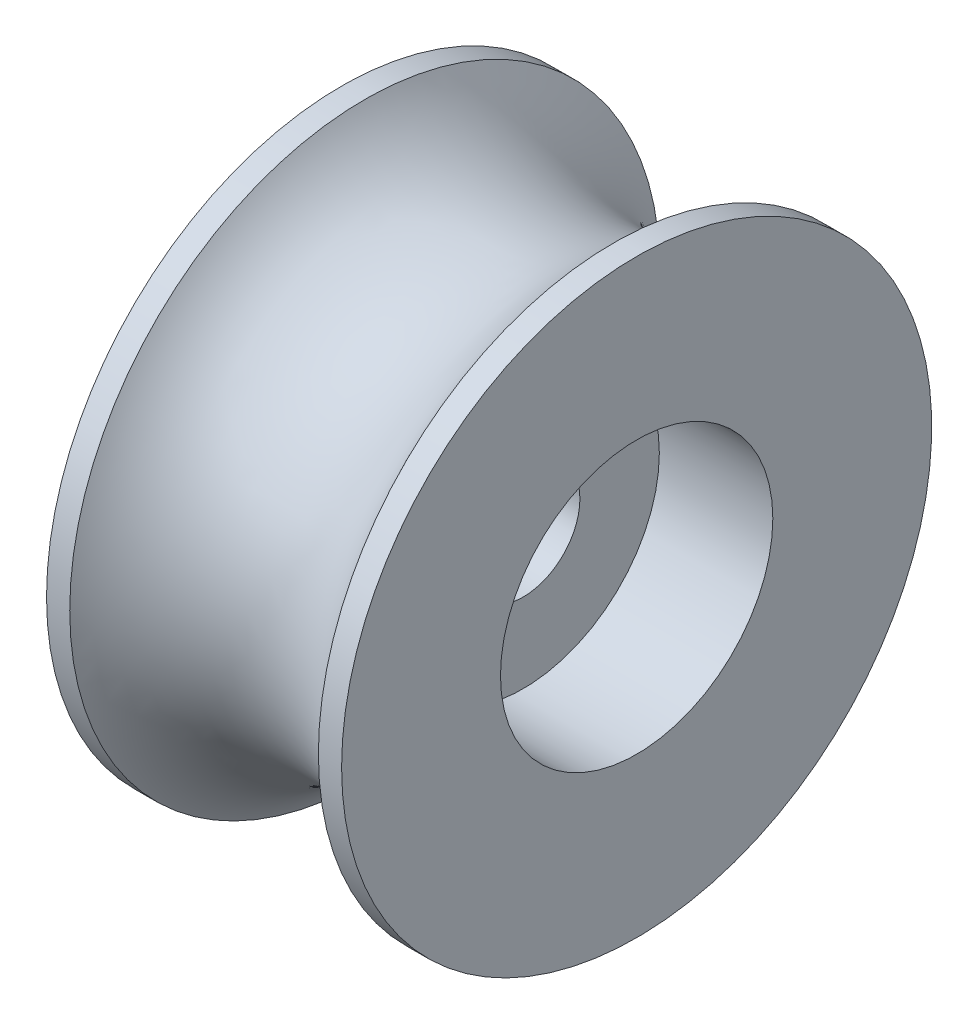
SolidWorks part; units mm, degrees
ref_plane "前视基准面" through (0, 0, 0) normal (0, 0, 1) x (1, 0, 0)
ref_plane "上视基准面" through (0, 0, 0) normal (0, 1, 0) x (1, 0, 0)
ref_plane "右视基准面" through (0, 0, 0) normal (1, 0, 0) x (0, 0, -1)
sketch "草图1" plane through (0, 0, 0) normal (0, 1, 0) x (1, 0, 0)
  line L0 (0, 10) -> (0, -6.5) construction
  line L1 (-6.5, 6.5) -> (6.5, 6.5) construction
  line L2 (-6.5, 6.5) -> (-6.5, -6.5)
  line L3 (-6.5, -6.5) -> (6.5, -6.5)
  line L4 (6.5, 6.5) -> (6.5, -6.5)
  line L5 (-6.5, 6.5) -> (6.5, -6.5) construction
  line L6 (-6.5, -6.5) -> (6.5, 6.5) construction
  line L7 (-5.4772, 6.5) -> (-6.5, 6.5)
  line L8 (5.4772, 6.5) -> (6.5, 6.5)
  line L9 (0, 3.5) -> (0, -6.5) construction
  circle A0 centre (0, 10) radius 6.5 construction
  arc A1 (-5.4772, 6.5) -> (5.4772, 6.5) centre (0, 10) ccw
  point P0 (0, 0)
  point P12 (0, 0)
  dimension "D3" = 13
  dimension "D1" = 10
  dimension "D2" = 13
  dimension "D4" = 13
revolve "旋转1" add sketch "草图1" angle 360 about L3
sketch "草图2" plane through (6.5, 0, 0) normal (1, 0, 0) x (0, 0, -1)
  circle A0 centre (-6.5, 0) radius 2.5
  dimension "D1" = 5
extrude "切除-拉伸1" cut sketch "草图2" against normal blind 55
sketch "草图3" plane through (6.5, 0, 0) normal (1, 0, 0) x (0, 0, -1)
  circle A0 centre (-6.5, 0) radius 6
  dimension "D1" = 12
extrude "切除-拉伸2" cut sketch "草图3" against normal blind 5
sketch "草图4" plane through (-6.5, 0, 0) normal (-1, 0, 0) x (0, 0, 1)
  circle A0 centre (6.5, 0) radius 6
  dimension "D1" = 12
extrude "切除-拉伸3" cut sketch "草图4" against normal blind 5
